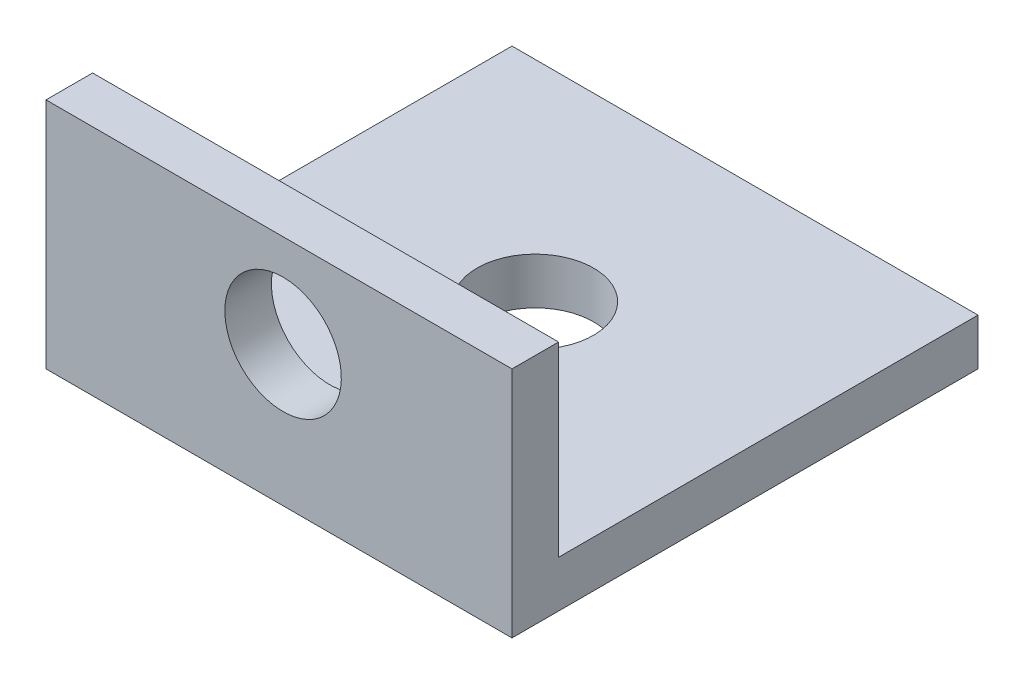
SolidWorks part; units mm, degrees
ref_plane "Front Plane" through (0, 0, 0) normal (0, 0, 1) x (1, 0, 0)
ref_plane "Top Plane" through (0, 0, 0) normal (0, 1, 0) x (1, 0, 0)
ref_plane "Right Plane" through (0, 0, 0) normal (1, 0, 0) x (0, 0, -1)
sketch "Sketch1" plane through (0, 0, 0) normal (1, 0, 0) x (0, 0, -1)
  line L0 (0, 10) -> (0, 0)
  line L1 (0, 0) -> (20, 0)
  line L2 (20, 0) -> (20, 2)
  line L3 (20, 2) -> (2, 2)
  line L4 (2, 2) -> (2, 10)
  line L5 (2, 10) -> (0, 10)
  dimension "D1" = 10
  dimension "D2" = 20
  dimension "D3" = 2
  dimension "D4" = 2
extrude "Boss-Extrude1" add sketch "Sketch1" along normal blind 20
sketch "Sketch2" plane through (0, 0, -2) normal (0, 0, -1) x (-1, 0, 0)
  line L0 (-20, 10) -> (0, 10) construction
  circle A0 centre (-10.1749, 6) radius 2.5
  dimension "D2" = 5
  dimension "D1" = 4
extrude "Cut-Extrude1" cut sketch "Sketch2" against normal blind 2
sketch "Sketch3" plane through (0, 2, 0) normal (0, 1, 0) x (1, 0, 0)
  line L0 (20, 20) -> (0, 20) construction
  line L1 (0, 20) -> (0, 2) construction
  circle A0 centre (10, 11) radius 2.5
  dimension "D3" = 5
  dimension "D1" = 9
  dimension "D2" = 10
extrude "Cut-Extrude2" cut sketch "Sketch3" against normal blind 2
